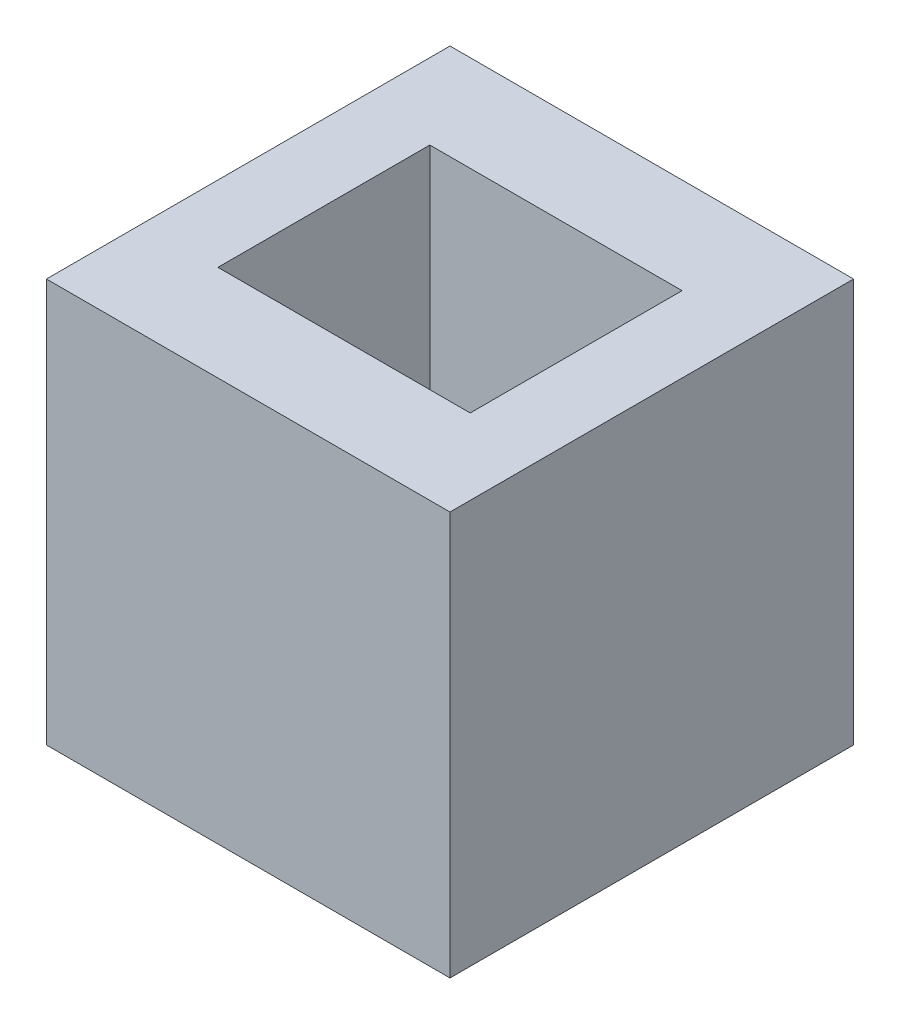
SolidWorks part; units mm, degrees
ref_plane "Front Plane" through (0, 0, 0) normal (0, 0, 1) x (1, 0, 0)
ref_plane "Top Plane" through (0, 0, 0) normal (0, 1, 0) x (1, 0, 0)
ref_plane "Right Plane" through (0, 0, 0) normal (1, 0, 0) x (0, 0, -1)
sketch "Sketch1" plane through (0, 0, 0) normal (0, 1, 0) x (1, 0, 0)
  line L1 (10, -10) -> (-10, -10)
  line L2 (10, -10) -> (10, 10)
  line L3 (10, 10) -> (-10, 10)
  line L4 (-10, -10) -> (-10, 10)
  line L5 (10, -10) -> (-10, 10) construction
  line L6 (10, 10) -> (-10, -10) construction
  line L7 (6.25, -5.25) -> (-6.25, -5.25)
  line L8 (6.25, -5.25) -> (6.25, 5.25)
  line L9 (6.25, 5.25) -> (-6.25, 5.25)
  line L10 (-6.25, -5.25) -> (-6.25, 5.25)
  line L11 (6.25, -5.25) -> (-6.25, 5.25) construction
  line L12 (6.25, 5.25) -> (-6.25, -5.25) construction
  point P0 (0, 0)
  point P6 (0, 0)
  dimension "D1" = 20
  dimension "D2" = 12.5
  dimension "D3" = 10.5
extrude "Boss-Extrude1" add sketch "Sketch1" along normal blind 20
